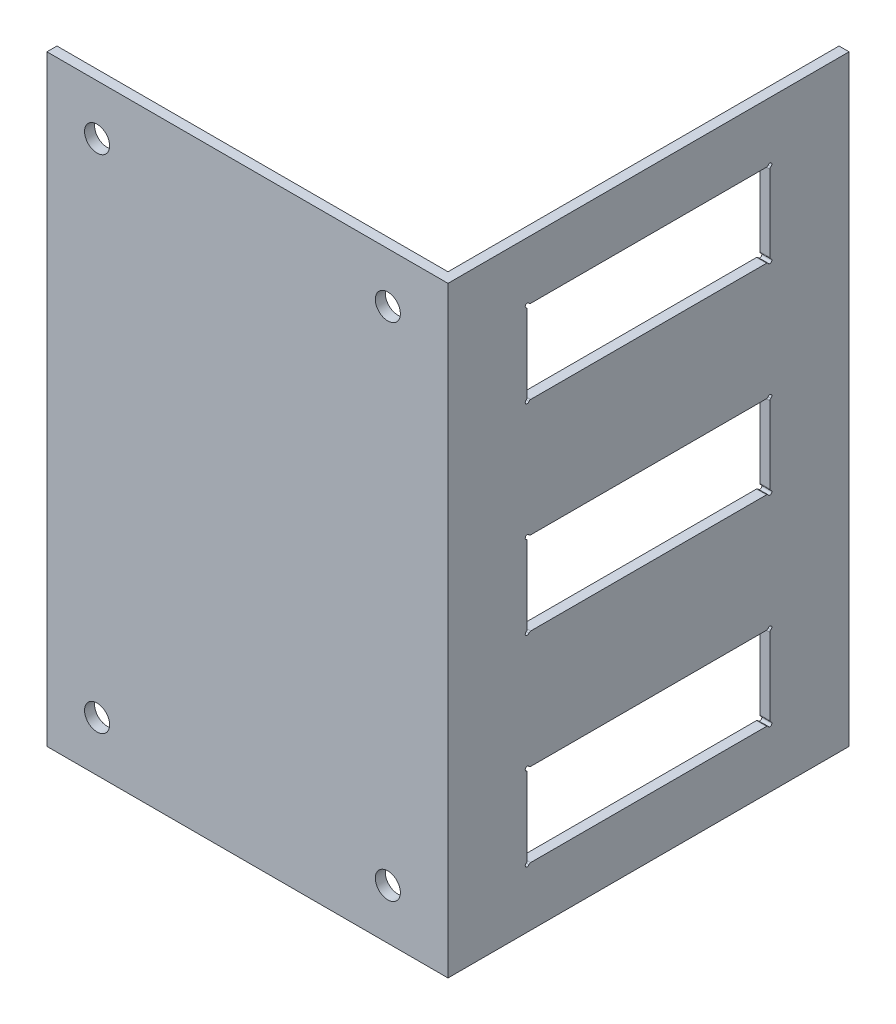
SolidWorks part; units mm, degrees
ref_plane "Front Plane" through (0, 0, 0) normal (0, 0, 1) x (1, 0, 0)
ref_plane "Top Plane" through (0, 0, 0) normal (0, 1, 0) x (1, 0, 0)
ref_plane "Right Plane" through (0, 0, 0) normal (1, 0, 0) x (0, 0, -1)
sketch "Sketch1" plane through (0, 0, 0) normal (0, 1, 0) x (1, 0, 0)
  line L0 (0, 0) -> (0, 1.27)
  line L1 (0, 1.27) -> (49.53, 1.27)
  line L2 (49.53, 1.27) -> (49.53, 50.8)
  line L3 (49.53, 50.8) -> (50.8, 50.8)
  line L4 (50.8, 50.8) -> (50.8, 0)
  line L5 (50.8, 0) -> (0, 0)
  dimension "D1" = 1.27
  dimension "D2" = 1.27
  dimension "D3" = 50.8
  dimension "D4" = 50.8
extrude "Boss-Extrude1" add sketch "Sketch1" along normal blind 76.2
ref_plane "Plane1" through (0, 38.1, 0) normal (0, 1, 0) x (1, 0, 0)
ref_plane "Plane2" through (0, 0, -25.4) normal (0, 0, 1) x (1, 0, 0)
sketch "Sketch2" plane through (49.53, 0, 0) normal (-1, 0, 0) x (0, 0, 1)
  line L0 (-40.767, 38.1) -> (-10.033, 38.1) construction
  line L1 (-25.4, 32.8295) -> (-25.4, 43.3705) construction
  line L2 (-10.033, 33.2625) -> (-10.033, 42.9375)
  line L3 (-10.466, 43.3705) -> (-40.334, 43.3705)
  line L4 (-10.033, 32.8295) -> (-10.033, 43.3705)
  line L5 (-40.767, 32.8295) -> (-10.033, 32.8295)
  line L6 (-40.767, 43.3705) -> (-40.767, 32.8295)
  line L7 (-10.033, 43.3705) -> (-40.767, 43.3705)
  line L8 (-10.033, 32.8295) -> (-10.033, 43.3705) construction
  line L9 (-40.767, 32.8295) -> (-10.033, 32.8295) construction
  line L10 (-40.767, 43.3705) -> (-40.767, 32.8295) construction
  line L11 (-10.033, 43.3705) -> (-40.767, 43.3705) construction
  line L12 (-40.767, 42.9375) -> (-40.767, 33.2625)
  line L13 (-40.334, 32.8295) -> (-10.466, 32.8295)
  line L14 (-10.033, 7.8625) -> (-10.033, 17.5375)
  line L15 (-10.466, 17.9705) -> (-40.334, 17.9705)
  line L16 (-40.767, 17.5375) -> (-40.767, 7.8625)
  line L17 (-40.334, 7.4295) -> (-10.466, 7.4295)
  line L18 (-40.767, 12.7) -> (-10.033, 12.7) construction
  line L19 (-25.4, 7.4295) -> (-25.4, 17.9705) construction
  line L20 (-10.033, 7.4295) -> (-10.033, 17.9705) construction
  line L21 (-40.767, 7.4295) -> (-10.033, 7.4295) construction
  line L22 (-40.767, 17.9705) -> (-40.767, 7.4295) construction
  line L23 (-10.033, 17.9705) -> (-40.767, 17.9705) construction
  line L24 (-10.033, 33.2625) -> (-10.033, 42.9375)
  line L25 (-10.466, 43.3705) -> (-40.334, 43.3705)
  line L26 (-40.767, 42.9375) -> (-40.767, 33.2625)
  line L27 (-40.334, 32.8295) -> (-10.466, 32.8295)
  line L28 (-40.767, 38.1) -> (-10.033, 38.1) construction
  line L29 (-25.4, 32.8295) -> (-25.4, 43.3705) construction
  line L30 (-10.033, 32.8295) -> (-10.033, 43.3705) construction
  line L31 (-40.767, 32.8295) -> (-10.033, 32.8295) construction
  line L32 (-40.767, 43.3705) -> (-40.767, 32.8295) construction
  line L33 (-10.033, 43.3705) -> (-40.767, 43.3705) construction
  line L34 (-10.033, 58.6625) -> (-10.033, 68.3375)
  line L35 (-10.466, 68.7705) -> (-40.334, 68.7705)
  line L36 (-40.767, 68.3375) -> (-40.767, 58.6625)
  line L37 (-40.334, 58.2295) -> (-10.466, 58.2295)
  line L38 (-40.767, 63.5) -> (-10.033, 63.5) construction
  line L39 (-25.4, 58.2295) -> (-25.4, 68.7705) construction
  line L40 (-10.033, 58.2295) -> (-10.033, 68.7705) construction
  line L41 (-40.767, 58.2295) -> (-10.033, 58.2295) construction
  line L42 (-40.767, 68.7705) -> (-40.767, 58.2295) construction
  line L43 (-10.033, 68.7705) -> (-40.767, 68.7705) construction
  line L44 (-10.033, 33.2625) -> (-10.033, 7.8625) construction
  line L45 (-10.033, 33.2625) -> (-10.033, 58.6625) construction
  arc A0 (-40.892, 33.046) -> (-40.5505, 32.7045) centre (-40.767, 32.8295) ccw
  arc A1 (-40.334, 32.8295) -> (-40.5505, 32.7045) centre (-40.334, 32.5795) ccw
  arc A2 (-40.892, 33.046) -> (-40.767, 33.2625) centre (-41.017, 33.2625) ccw
  arc A3 (-40.892, 43.154) -> (-40.767, 42.9375) centre (-41.017, 42.9375) cw
  arc A4 (-40.334, 43.3705) -> (-40.5505, 43.4955) centre (-40.334, 43.6205) cw
  arc A5 (-40.892, 43.154) -> (-40.5505, 43.4955) centre (-40.767, 43.3705) cw
  arc A6 (-9.908, 43.154) -> (-10.2495, 43.4955) centre (-10.033, 43.3705) ccw
  arc A7 (-10.466, 43.3705) -> (-10.2495, 43.4955) centre (-10.466, 43.6205) ccw
  arc A8 (-9.908, 43.154) -> (-10.033, 42.9375) centre (-9.783, 42.9375) ccw
  arc A9 (-9.908, 33.046) -> (-10.033, 33.2625) centre (-9.783, 33.2625) cw
  arc A10 (-10.466, 32.8295) -> (-10.2495, 32.7045) centre (-10.466, 32.5795) cw
  arc A11 (-9.908, 33.046) -> (-10.2495, 32.7045) centre (-10.033, 32.8295) cw
  arc A12 (-40.892, 7.646) -> (-40.5505, 7.3045) centre (-40.767, 7.4295) ccw
  arc A13 (-40.334, 7.4295) -> (-40.5505, 7.3045) centre (-40.334, 7.1795) ccw
  arc A14 (-40.892, 7.646) -> (-40.767, 7.8625) centre (-41.017, 7.8625) ccw
  arc A15 (-40.892, 17.754) -> (-40.767, 17.5375) centre (-41.017, 17.5375) cw
  arc A16 (-40.334, 17.9705) -> (-40.5505, 18.0955) centre (-40.334, 18.2205) cw
  arc A17 (-40.892, 17.754) -> (-40.5505, 18.0955) centre (-40.767, 17.9705) cw
  arc A18 (-9.908, 17.754) -> (-10.2495, 18.0955) centre (-10.033, 17.9705) ccw
  arc A19 (-10.466, 17.9705) -> (-10.2495, 18.0955) centre (-10.466, 18.2205) ccw
  arc A20 (-9.908, 17.754) -> (-10.033, 17.5375) centre (-9.783, 17.5375) ccw
  arc A21 (-9.908, 7.646) -> (-10.033, 7.8625) centre (-9.783, 7.8625) cw
  arc A22 (-10.466, 7.4295) -> (-10.2495, 7.3045) centre (-10.466, 7.1795) cw
  arc A23 (-9.908, 7.646) -> (-10.2495, 7.3045) centre (-10.033, 7.4295) cw
  arc A24 (-40.892, 33.046) -> (-40.5505, 32.7045) centre (-40.767, 32.8295) ccw
  arc A25 (-40.334, 32.8295) -> (-40.5505, 32.7045) centre (-40.334, 32.5795) ccw
  arc A26 (-40.892, 33.046) -> (-40.767, 33.2625) centre (-41.017, 33.2625) ccw
  arc A27 (-40.892, 43.154) -> (-40.767, 42.9375) centre (-41.017, 42.9375) cw
  arc A28 (-40.334, 43.3705) -> (-40.5505, 43.4955) centre (-40.334, 43.6205) cw
  arc A29 (-40.892, 43.154) -> (-40.5505, 43.4955) centre (-40.767, 43.3705) cw
  arc A30 (-9.908, 43.154) -> (-10.2495, 43.4955) centre (-10.033, 43.3705) ccw
  arc A31 (-10.466, 43.3705) -> (-10.2495, 43.4955) centre (-10.466, 43.6205) ccw
  arc A32 (-9.908, 43.154) -> (-10.033, 42.9375) centre (-9.783, 42.9375) ccw
  arc A33 (-9.908, 33.046) -> (-10.033, 33.2625) centre (-9.783, 33.2625) cw
  arc A34 (-10.466, 32.8295) -> (-10.2495, 32.7045) centre (-10.466, 32.5795) cw
  arc A35 (-9.908, 33.046) -> (-10.2495, 32.7045) centre (-10.033, 32.8295) cw
  arc A36 (-40.892, 58.446) -> (-40.5505, 58.1045) centre (-40.767, 58.2295) ccw
  arc A37 (-40.334, 58.2295) -> (-40.5505, 58.1045) centre (-40.334, 57.9795) ccw
  arc A38 (-40.892, 58.446) -> (-40.767, 58.6625) centre (-41.017, 58.6625) ccw
  arc A39 (-40.892, 68.554) -> (-40.767, 68.3375) centre (-41.017, 68.3375) cw
  arc A40 (-40.334, 68.7705) -> (-40.5505, 68.8955) centre (-40.334, 69.0205) cw
  arc A41 (-40.892, 68.554) -> (-40.5505, 68.8955) centre (-40.767, 68.7705) cw
  arc A42 (-9.908, 68.554) -> (-10.2495, 68.8955) centre (-10.033, 68.7705) ccw
  arc A43 (-10.466, 68.7705) -> (-10.2495, 68.8955) centre (-10.466, 69.0205) ccw
  arc A44 (-9.908, 68.554) -> (-10.033, 68.3375) centre (-9.783, 68.3375) ccw
  arc A45 (-9.908, 58.446) -> (-10.033, 58.6625) centre (-9.783, 58.6625) cw
  arc A46 (-10.466, 58.2295) -> (-10.2495, 58.1045) centre (-10.466, 57.9795) cw
  arc A47 (-9.908, 58.446) -> (-10.2495, 58.1045) centre (-10.033, 58.2295) cw
  dimension "D2" = 0.5
  dimension "D5" = 25.4
  dimension "D6" = 25.4
  dimension "D1" = 0
  dimension "D3" = 2
  dimension "D4" = 2
extrude "Cut-Extrude1" cut sketch "Sketch2" against normal through all contours A47 A45 L34 A44 A42 A43 L35 A40 A41 A39 L36 A38 A36 A37 L37 A46 | A11 A9 L2 A8 A6 A7 L3 A4 A5 A3 L12 A2 A0 A1 L13 A10 | A23 A21 L14 A20 A18 A19 L15 A16 A17 A15 L16 A14 A12 A13 L17 A22
sketch "Sketch3" plane through (0, 0, -1.27) normal (0, 0, -1) x (-1, 0, 0)
  line L0 (0, 0) -> (-49.53, 76.2) construction
  line L2 (-43.18, 6.35) -> (-6.35, 6.35) construction
  line L3 (-43.18, 6.35) -> (-43.18, 69.85) construction
  line L4 (-49.53, 0) -> (0, 0)
  line L5 (0, 0) -> (0, 76.2)
  line L6 (0, 76.2) -> (-49.53, 76.2)
  line L7 (-49.53, 76.2) -> (-49.53, 0)
  line L8 (-49.53, 0) -> (0, 0) construction
  line L9 (0, 0) -> (0, 76.2) construction
  line L10 (0, 76.2) -> (-49.53, 76.2) construction
  line L11 (-49.53, 76.2) -> (-49.53, 0) construction
  line L12 (-43.18, 69.85) -> (-6.35, 69.85) construction
  line L13 (-6.35, 6.35) -> (-6.35, 69.85) construction
  line L14 (-43.18, 6.35) -> (-6.35, 69.85) construction
  line L15 (-43.18, 69.85) -> (-6.35, 6.35) construction
  circle A0 centre (-6.35, 69.85) radius 1.5875
  circle A1 centre (-6.35, 6.35) radius 1.5875
  circle A2 centre (-43.18, 6.35) radius 1.5875
  circle A3 centre (-43.18, 69.85) radius 1.5875
  point P2 (-24.765, 38.1)
  dimension "D4" = 3.175
  dimension "D2" = 6.35
  dimension "D3" = 6.35
  dimension "D1" = 0
extrude "Cut-Extrude2" cut sketch "Sketch3" against normal through all
equation "\"D2@Sketch1\"=\"D1@Sketch1\""
equation "\"D4@Sketch1\"=\"D3@Sketch1\""
